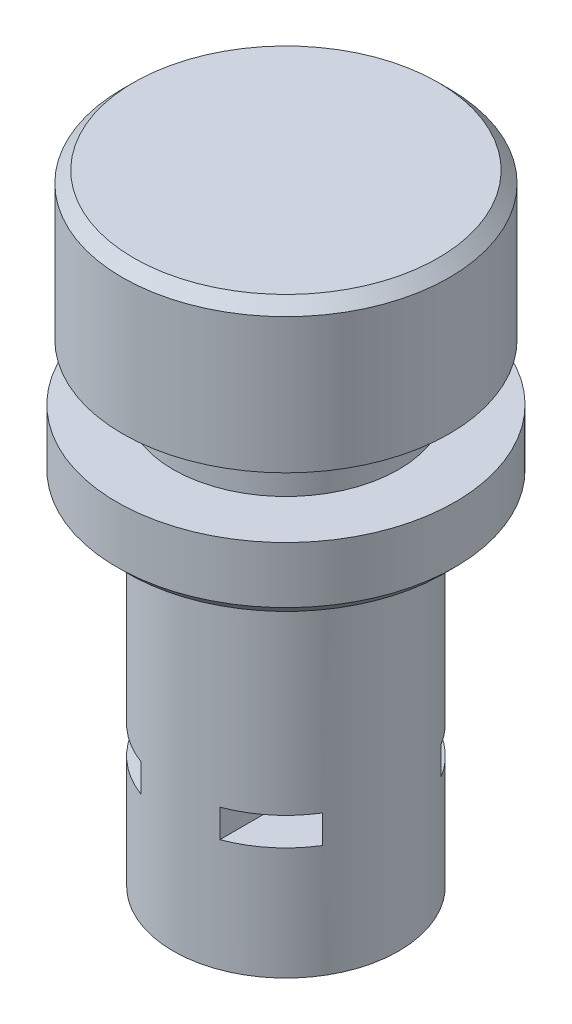
SolidWorks part; units mm, degrees
ref_plane "Спереди" through (0, 0, 0) normal (0, 0, 1) x (1, 0, 0)
ref_plane "Сверху" through (0, 0, 0) normal (0, 1, 0) x (1, 0, 0)
ref_plane "Справа" through (0, 0, 0) normal (1, 0, 0) x (0, 0, -1)
other "Configuration Table"
sketch "Эскиз1" plane through (0, 0, 0) normal (0, 1, 0) x (1, 0, 0)
  circle A0 centre (0, 0) radius 14.5
  dimension "D1" = 29
extrude "Бобышка-Вытянуть1" add sketch "Эскиз1" along normal blind 13
chamfer "Фаска1" distance 1 angle 45 1 edges at (0, 13, 14.5)
sketch "Эскиз2" plane through (0, 0, 0) normal (0, -1, 0) x (1, 0, 0)
  circle A0 centre (0, 0) radius 10
  dimension "D1" = 20
extrude "Бобышка-Вытянуть2" add sketch "Эскиз2" along normal blind 42
cosmetic thread "Условное изображение резьбы1" parameters "D1"=10, "D2"=4.11
sketch "Эскиз3" plane through (0, 0, 0) normal (0, 0, 1) x (1, 0, 0)
  line L0 (0, 0) -> (0, -42) construction
  line L1 (-10, -42) -> (10, -42) construction
  line L2 (8.5, -32) -> (3.5, -29.5) construction
  line L3 (-8.5, -29.5) -> (-3.5, -29.5)
  line L4 (-8.5, -29.5) -> (-8.5, -32)
  line L5 (-8.5, -32) -> (-3.5, -32)
  line L6 (-3.5, -29.5) -> (-3.5, -32)
  line L7 (-8.5, -29.5) -> (-3.5, -32) construction
  line L8 (-8.5, -32) -> (-3.5, -29.5) construction
  line L9 (8.5, -29.5) -> (3.5, -32) construction
  line L10 (3.5, -29.5) -> (3.5, -32)
  line L11 (8.5, -32) -> (3.5, -32)
  line L12 (8.5, -29.5) -> (8.5, -32)
  line L13 (8.5, -29.5) -> (3.5, -29.5)
  point P5 (-6, -30.75)
  dimension "D1" = 5
  dimension "D2" = 2.5
  dimension "D3" = 6
  dimension "D4" = 10
extrude "Вырез-Вытянуть1" cut sketch "Эскиз3" against normal through all both and the other way through all
sketch "Эскиз5" plane through (0, -32, 0) normal (0, 1, 0) x (1, 0, 0)
  circle A0 centre (6, 0) radius 1
  point P2 (0, 0)
  dimension "D1" = 2
  dimension "D2" = 6
extrude "Бобышка-Вытянуть3" add sketch "Эскиз5" along normal up to next
mirror "Зеркальное отражение1" about plane through (0, 0, 0) normal (1, 0, 0) of "Бобышка-Вытянуть3"
sketch "Эскиз6" plane through (0, 0, 0) normal (0, -1, 0) x (1, 0, 0)
  circle A0 centre (0, 0) radius 15
  dimension "D1" = 30
extrude "Бобышка-Вытянуть4" add sketch "Эскиз6" along normal blind 6 from offset 5
chamfer "Фаска3" distance 1 angle 45 1 edges at (0, -11, -15)
